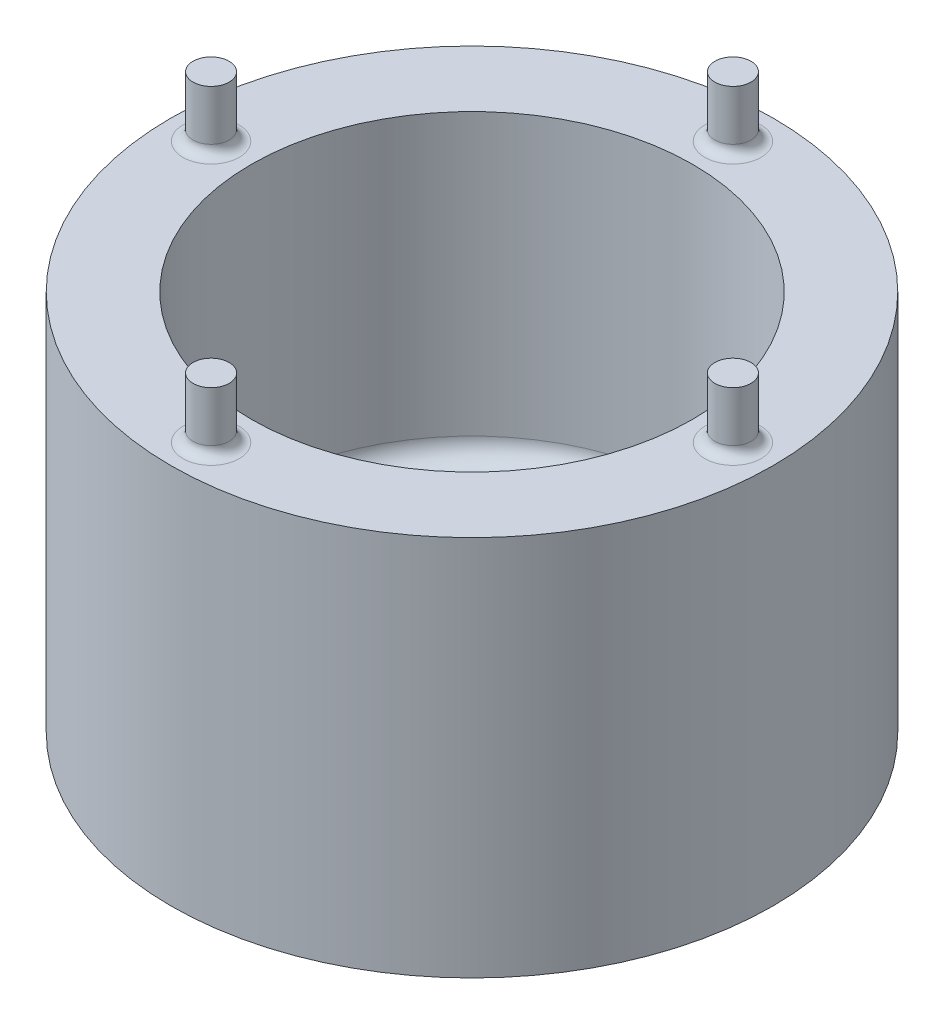
SolidWorks part; units mm, degrees
ref_plane "Front Plane" through (0, 0, 0) normal (0, 0, 1) x (1, 0, 0)
ref_plane "Top Plane" through (0, 0, 0) normal (0, 1, 0) x (1, 0, 0)
ref_plane "Right Plane" through (0, 0, 0) normal (1, 0, 0) x (0, 0, -1)
sketch "Sketch1" plane through (0, 0, 0) normal (0, 1, 0) x (1, 0, 0)
  circle A1 centre (0, 0) radius 15
  dimension "D2" = 30
extrude "Boss-Extrude1" add sketch "Sketch1" along normal blind 4 contours A1
sketch "Sketch2" plane through (0, 4, 0) normal (0, 1, 0) x (1, 0, 0)
  circle A0 centre (0, 0) radius 15
  circle A1 centre (0, 0) radius 11
  circle A2 centre (0, 0) radius 15 construction
  dimension "D1" = 4
extrude "Boss-Extrude2" add sketch "Sketch2" along normal blind 15
sketch "Sketch3" plane through (0, 19, 0) normal (0, 1, 0) x (1, 0, 0)
  line L0 (0, -10.45) -> (0, 10.45) construction
  line L1 (-10.45, 0) -> (10.45, 0) construction
  circle A0 centre (0, -13) radius 0.9
  dimension "D1" = 1.8
  dimension "D2" = 13
extrude "Boss-Extrude3" add sketch "Sketch3" along normal blind 3
fillet "Fillet1" radius 0.5 1 edges at (0, 19, 13.9)
pattern_circular "CirPattern1" count 4 every 90 about axis through (0, 0, 0) along (0, 1, 0) of "Boss-Extrude3", "Fillet1"
fillet "Fillet2" radius 1 1 edges at (0, 4, 11)
